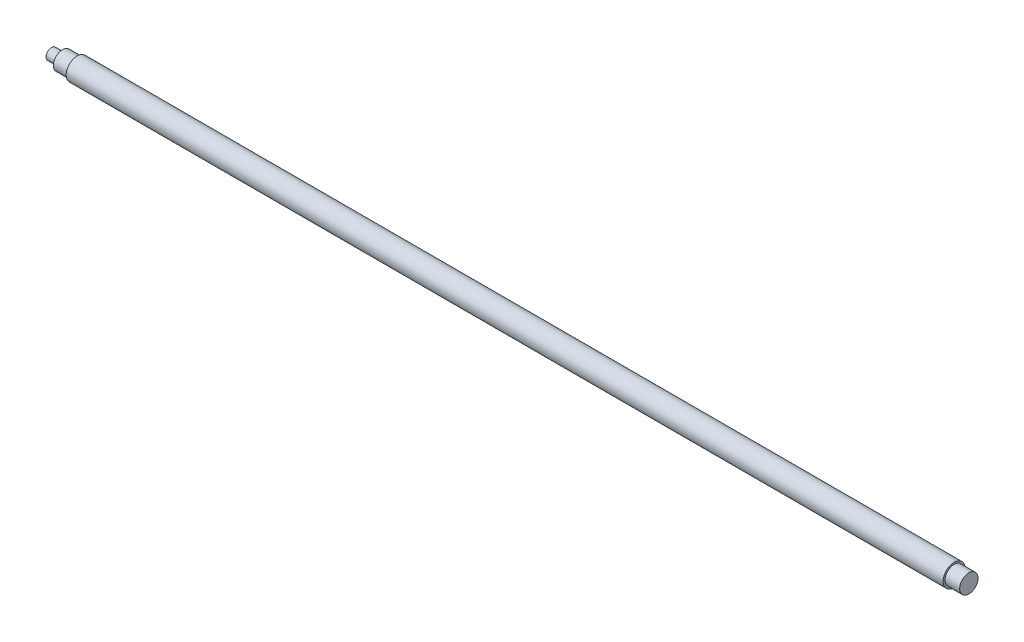
SolidWorks part; units mm, degrees
ref_plane "Plano frontal" through (0, 0, 0) normal (0, 0, 1) x (1, 0, 0)
ref_plane "Plano superior" through (0, 0, 0) normal (0, 1, 0) x (1, 0, 0)
ref_plane "Plano direito" through (0, 0, 0) normal (1, 0, 0) x (0, 0, -1)
sketch "Esboço2" plane through (0, 0, 0) normal (0, 0, 1) x (1, 0, 0)
  line L0 (0, 0) -> (500, 0)
  line L1 (0, 0) -> (0, 3)
  line L2 (0, 3) -> (6, 3)
  line L3 (6, 3) -> (6, 5)
  line L4 (6, 5) -> (14, 5)
  line L5 (14, 5) -> (14, 6)
  line L6 (14, 6) -> (492, 6)
  line L7 (492, 6) -> (492, 5)
  line L8 (492, 5) -> (500, 5)
  line L9 (500, 5) -> (500, 0)
  dimension "D1" = 3
  dimension "D2" = 5
  dimension "D3" = 6
  dimension "D4" = 5
  dimension "D5" = 8
  dimension "D6" = 6
  dimension "D7" = 8
  dimension "D8" = 500
revolve "Revolução1" add sketch "Esboço2" angle 360 about L0
